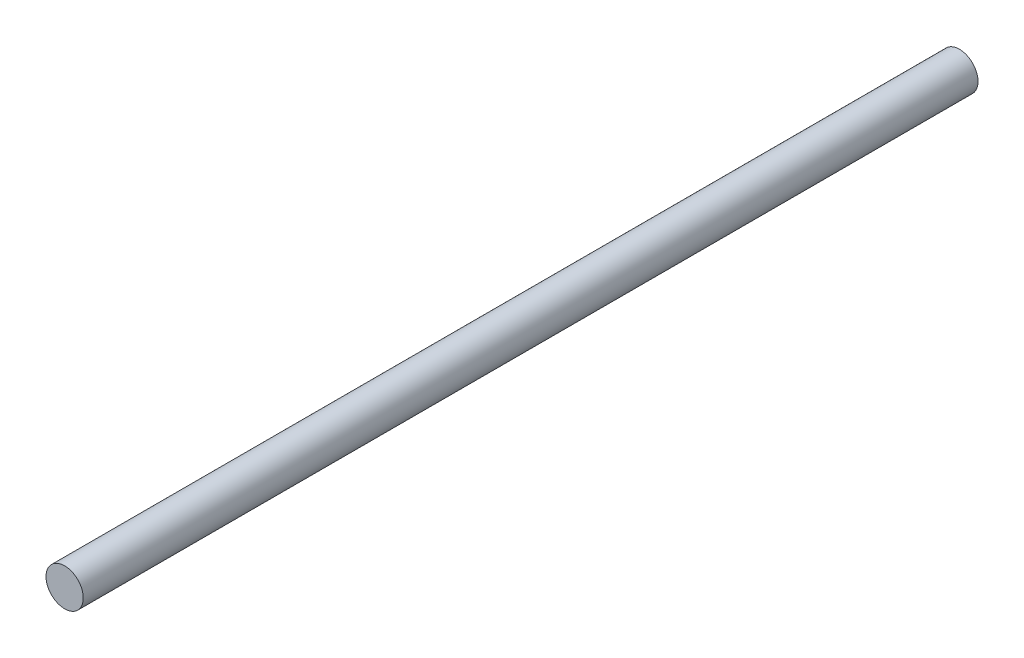
SolidWorks part; units mm, degrees
material "6061-T6 (SS)"
ref_plane "Front Plane" through (0, 0, 0) normal (0, 0, 1) x (1, 0, 0)
ref_plane "Top Plane" through (0, 0, 0) normal (0, 1, 0) x (1, 0, 0)
ref_plane "Right Plane" through (0, 0, 0) normal (1, 0, 0) x (0, 0, -1)
sketch "Sketch1" plane through (0, 0, 0) normal (0, 0, 1) x (1, 0, 0)
  circle A0 centre (0, 0) radius 1.5875
  dimension "D1" = 3.175
extrude "Boss-Extrude1" add sketch "Sketch1" along normal blind 76.2
